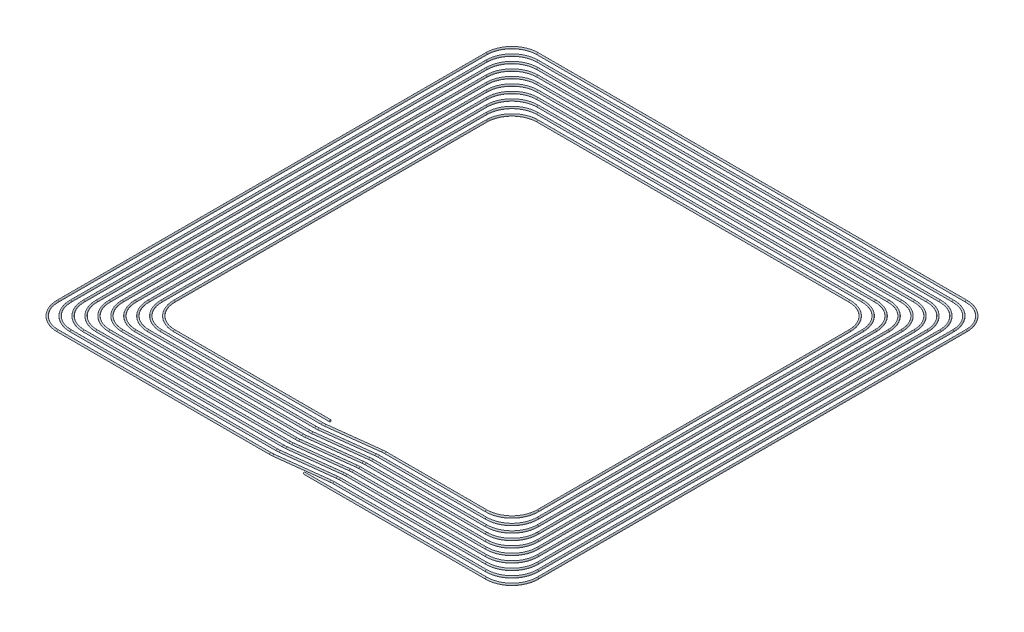
SolidWorks part; units mm, degrees
ref_plane "前视基准面" through (0, 0, 0) normal (0, 0, 1) x (1, 0, 0)
ref_plane "上视基准面" through (0, 0, 0) normal (0, 1, 0) x (1, 0, 0)
ref_plane "右视基准面" through (0, 0, 0) normal (1, 0, 0) x (0, 0, -1)
sketch "草图1" plane through (0, 0, 0) normal (0, 1, 0) x (1, 0, 0)
  line L0 (18.78, -3.78) -> (261.22, -3.78)
  line L1 (15, 0) -> (265, 0)
  line L2 (0, -15) -> (0, -265)
  line L3 (15, -280) -> (139.1015, -280)
  line L4 (280, -15) -> (280, -265)
  line L5 (276.22, -18.78) -> (276.22, -261.22)
  line L6 (18.78, -276.22) -> (139.1015, -276.22)
  line L7 (3.78, -18.78) -> (3.78, -261.22)
  line L8 (22.56, -7.56) -> (257.44, -7.56)
  line L9 (272.44, -22.56) -> (272.44, -257.44)
  line L10 (22.56, -272.44) -> (139.1015, -272.44)
  line L11 (7.56, -22.56) -> (7.56, -257.44)
  line L12 (26.34, -11.34) -> (253.66, -11.34)
  line L13 (268.66, -26.34) -> (268.66, -253.66)
  line L14 (26.34, -268.66) -> (139.1015, -268.66)
  line L15 (11.34, -26.34) -> (11.34, -253.66)
  line L16 (30.12, -15.12) -> (249.88, -15.12)
  line L17 (264.88, -30.12) -> (264.88, -249.88)
  line L18 (30.12, -264.88) -> (139.1015, -264.88)
  line L19 (15.12, -30.12) -> (15.12, -249.88)
  line L20 (15, -276.22) -> (265, -276.22) construction
  line L21 (3.78, -15) -> (3.78, -265) construction
  line L22 (7.56, -15) -> (7.56, -265) construction
  line L23 (15, -272.44) -> (265, -272.44) construction
  line L24 (15, -268.66) -> (265, -268.66) construction
  line L25 (11.34, -15) -> (11.34, -265) construction
  line L26 (15.12, -15.12) -> (15.12, -264.88) construction
  line L27 (15.12, -264.88) -> (264.88, -264.88) construction
  line L28 (15, -280) -> (265, -280) construction
  line L29 (280, -15) -> (280, -265) construction
  line L30 (276.22, -15) -> (276.22, -265) construction
  line L31 (272.44, -15) -> (272.44, -265) construction
  line L32 (268.66, -15) -> (268.66, -265) construction
  line L33 (264.88, -15.12) -> (264.88, -264.88) construction
  line L34 (15, -3.78) -> (265, -3.78) construction
  line L35 (15, -7.56) -> (265, -7.56) construction
  line L36 (15, -11.34) -> (265, -11.34) construction
  line L37 (15.12, -15.12) -> (264.88, -15.12) construction
  line L38 (33.9, -18.9) -> (246.1, -18.9)
  line L39 (261.1, -33.9) -> (261.1, -246.1)
  line L40 (33.9, -261.1) -> (139.1015, -261.1)
  line L41 (18.9, -33.9) -> (18.9, -246.1)
  line L42 (37.68, -22.68) -> (242.32, -22.68)
  line L43 (257.32, -37.68) -> (257.32, -242.32)
  line L44 (37.68, -257.32) -> (139.1015, -257.32)
  line L45 (22.68, -37.68) -> (22.68, -242.32)
  line L46 (41.46, -26.46) -> (238.54, -26.46)
  line L47 (253.54, -41.46) -> (253.54, -238.54)
  line L48 (41.46, -253.54) -> (139.1015, -253.54)
  line L49 (26.46, -41.46) -> (26.46, -238.54)
  line L50 (45.24, -30.24) -> (234.76, -30.24)
  line L51 (249.76, -45.24) -> (249.76, -234.76)
  line L52 (45.24, -249.76) -> (139.1015, -249.76)
  line L53 (30.24, -45.24) -> (30.24, -234.76)
  line L54 (49.02, -34.02) -> (230.98, -34.02)
  line L55 (245.98, -49.02) -> (245.98, -230.98)
  line L56 (49.02, -245.98) -> (140, -245.98)
  line L57 (34.02, -49.02) -> (34.02, -230.98)
  line L58 (34.02, -34.02) -> (245.98, -34.02) construction
  line L59 (245.98, -34.02) -> (245.98, -245.98) construction
  line L60 (30.24, -30.24) -> (249.76, -30.24) construction
  line L61 (249.76, -30.24) -> (249.76, -249.76) construction
  line L62 (30.12, -26.46) -> (249.88, -26.46) construction
  line L63 (253.54, -30.12) -> (253.54, -249.88) construction
  line L64 (30.12, -22.68) -> (249.88, -22.68) construction
  line L65 (257.32, -30.12) -> (257.32, -249.88) construction
  line L66 (30.12, -18.9) -> (249.88, -18.9) construction
  line L67 (261.1, -30.12) -> (261.1, -249.88) construction
  line L68 (34.02, -245.98) -> (245.98, -245.98) construction
  line L69 (30.24, -249.76) -> (249.76, -249.76) construction
  line L70 (30.12, -253.54) -> (249.88, -253.54) construction
  line L71 (30.12, -257.32) -> (249.88, -257.32) construction
  line L72 (30.12, -261.1) -> (249.88, -261.1) construction
  line L73 (34.02, -34.02) -> (34.02, -245.98) construction
  line L74 (30.24, -30.24) -> (30.24, -249.76) construction
  line L75 (26.46, -30.12) -> (26.46, -249.88) construction
  line L76 (22.68, -30.12) -> (22.68, -249.88) construction
  line L77 (18.9, -30.12) -> (18.9, -249.88) construction
  line L78 (140.8921, -279.8927) -> (170.5473, -276.3273)
  line L79 (140, -281.3464) -> (140, -242.32) construction
  line L80 (158.8189, -280) -> (265, -280)
  line L81 (140.8921, -276.1127) -> (170.5473, -272.5473)
  line L82 (140.8921, -272.3327) -> (170.5473, -268.7673)
  line L83 (140.8921, -268.5527) -> (170.5473, -264.9873)
  line L84 (140.8921, -264.7727) -> (170.5473, -261.2073)
  line L85 (172.3379, -249.76) -> (234.76, -249.76)
  line L86 (140.8921, -253.4327) -> (170.5473, -249.8673)
  line L87 (140.8921, -249.6527) -> (170.5473, -246.0873)
  line L88 (140.8921, -260.9927) -> (170.5473, -257.4273)
  line L89 (140.8921, -257.2127) -> (170.5473, -253.6473)
  line L90 (172.3379, -245.98) -> (230.98, -245.98)
  line L91 (172.3379, -253.54) -> (238.54, -253.54)
  line L92 (172.3379, -257.32) -> (242.32, -257.32)
  line L93 (172.3379, -261.1) -> (246.1, -261.1)
  line L94 (172.3379, -264.88) -> (249.88, -264.88)
  line L95 (172.3379, -268.66) -> (253.66, -268.66)
  line L96 (30.12, -264.88) -> (249.88, -264.88) construction
  line L97 (172.3379, -272.44) -> (257.44, -272.44)
  line L98 (172.3379, -276.22) -> (261.22, -276.22)
  arc A0 (0, -265) -> (15, -280) centre (15, -265) ccw
  arc A1 (265, -280) -> (280, -265) centre (265, -265) ccw
  arc A2 (265, 0) -> (280, -15) centre (265, -15) cw
  arc A3 (15, 0) -> (0, -15) centre (15, -15) ccw
  arc A4 (139.1015, -261.1) -> (140.8921, -260.9927) centre (139.1015, -246.1) ccw
  arc A5 (139.1015, -264.88) -> (140.8921, -264.7727) centre (139.1015, -249.88) ccw
  arc A6 (139.1015, -268.66) -> (140.8921, -268.5527) centre (139.1015, -253.66) ccw
  arc A7 (139.1015, -272.44) -> (140.8921, -272.3327) centre (139.1015, -257.44) ccw
  arc A8 (139.1015, -276.22) -> (140.8921, -276.1127) centre (139.1015, -261.22) ccw
  arc A9 (139.1015, -280) -> (140.8921, -279.8927) centre (139.1015, -265) ccw
  arc A10 (170.5473, -276.3273) -> (172.3379, -276.22) centre (172.3379, -291.22) cw
  arc A11 (170.5473, -272.5473) -> (172.3379, -272.44) centre (172.3379, -287.44) cw
  arc A12 (170.5473, -268.7673) -> (172.3379, -268.66) centre (172.3379, -283.66) cw
  arc A13 (170.5473, -264.9873) -> (172.3379, -264.88) centre (172.3379, -279.88) cw
  arc A14 (170.5473, -261.2073) -> (172.3379, -261.1) centre (172.3379, -276.1) cw
  arc A15 (170.5473, -257.4273) -> (172.3379, -257.32) centre (172.3379, -272.32) cw
  arc A16 (30.12, -15.12) -> (15.12, -30.12) centre (30.12, -30.12) ccw
  arc A17 (276.22, -18.78) -> (261.22, -3.78) centre (261.22, -18.78) ccw
  arc A18 (265, -280) -> (280, -265) centre (265, -265) ccw
  arc A19 (26.34, -11.34) -> (11.34, -26.34) centre (26.34, -26.34) ccw
  arc A20 (18.78, -276.22) -> (3.78, -261.22) centre (18.78, -261.22) cw
  arc A21 (7.56, -257.44) -> (22.56, -272.44) centre (22.56, -257.44) ccw
  arc A22 (26.34, -268.66) -> (11.34, -253.66) centre (26.34, -253.66) cw
  arc A23 (15.12, -249.88) -> (30.12, -264.88) centre (30.12, -249.88) ccw
  arc A24 (15.12, -264.88) -> (15.12, -264.88) centre (15.12, -264.88) ccw construction
  arc A25 (261.22, -276.22) -> (276.22, -261.22) centre (261.22, -261.22) ccw
  arc A26 (257.44, -272.44) -> (272.44, -257.44) centre (257.44, -257.44) ccw
  arc A27 (253.66, -268.66) -> (268.66, -253.66) centre (253.66, -253.66) ccw
  arc A28 (249.88, -264.88) -> (264.88, -249.88) centre (249.88, -249.88) ccw
  arc A29 (264.88, -264.88) -> (264.88, -264.88) centre (264.88, -264.88) ccw construction
  arc A30 (272.44, -22.56) -> (257.44, -7.56) centre (257.44, -22.56) ccw
  arc A31 (268.66, -26.34) -> (253.66, -11.34) centre (253.66, -26.34) ccw
  arc A32 (249.88, -15.12) -> (264.88, -30.12) centre (249.88, -30.12) cw
  arc A33 (264.88, -15.12) -> (264.88, -15.12) centre (264.88, -15.12) cw construction
  arc A34 (15.12, -15.12) -> (15.12, -15.12) centre (15.12, -15.12) ccw construction
  arc A35 (22.56, -7.56) -> (7.56, -22.56) centre (22.56, -22.56) ccw
  arc A36 (18.78, -3.78) -> (3.78, -18.78) centre (18.78, -18.78) ccw
  arc A37 (15, -3.78) -> (3.78, -15) centre (15, -15) ccw construction
  arc A38 (15, -7.56) -> (7.56, -15) centre (15, -15) ccw construction
  arc A39 (15, -11.34) -> (11.34, -15) centre (15, -15) ccw construction
  arc A40 (265, -3.78) -> (276.22, -15) centre (265, -15) cw construction
  arc A41 (265, -7.56) -> (272.44, -15) centre (265, -15) cw construction
  arc A42 (265, -11.34) -> (268.66, -15) centre (265, -15) cw construction
  arc A43 (265, -272.44) -> (272.44, -265) centre (265, -265) ccw construction
  arc A44 (265, -276.22) -> (276.22, -265) centre (265, -265) ccw construction
  arc A45 (265, -268.66) -> (268.66, -265) centre (265, -265) ccw construction
  arc A46 (3.78, -265) -> (15, -276.22) centre (15, -265) ccw construction
  arc A47 (7.56, -265) -> (15, -272.44) centre (15, -265) ccw construction
  arc A48 (11.34, -265) -> (15, -268.66) centre (15, -265) ccw construction
  arc A49 (170.5473, -253.6473) -> (172.3379, -253.54) centre (172.3379, -268.54) cw
  arc A50 (139.1015, -257.32) -> (140.8921, -257.2127) centre (139.1015, -242.32) ccw
  arc A51 (139.1015, -253.54) -> (140.8921, -253.4327) centre (139.1015, -238.54) ccw
  arc A52 (170.5473, -249.8673) -> (172.3379, -249.76) centre (172.3379, -264.76) cw
  arc A53 (234.76, -30.24) -> (249.76, -45.24) centre (234.76, -45.24) cw
  arc A54 (234.76, -249.76) -> (249.76, -234.76) centre (234.76, -234.76) ccw
  arc A55 (30.24, -234.76) -> (45.24, -249.76) centre (45.24, -234.76) ccw
  arc A56 (45.24, -30.24) -> (30.24, -45.24) centre (45.24, -45.24) ccw
  arc A57 (230.98, -34.02) -> (245.98, -49.02) centre (230.98, -49.02) cw
  arc A58 (245.98, -34.02) -> (245.98, -34.02) centre (245.98, -34.02) cw construction
  arc A59 (238.54, -26.46) -> (253.54, -41.46) centre (238.54, -41.46) cw
  arc A60 (242.32, -22.68) -> (257.32, -37.68) centre (242.32, -37.68) cw
  arc A61 (246.1, -18.9) -> (261.1, -33.9) centre (246.1, -33.9) cw
  arc A62 (230.98, -245.98) -> (245.98, -230.98) centre (230.98, -230.98) ccw
  arc A63 (245.98, -245.98) -> (245.98, -245.98) centre (245.98, -245.98) ccw construction
  arc A64 (238.54, -253.54) -> (253.54, -238.54) centre (238.54, -238.54) ccw
  arc A65 (242.32, -257.32) -> (257.32, -242.32) centre (242.32, -242.32) ccw
  arc A66 (246.1, -261.1) -> (261.1, -246.1) centre (246.1, -246.1) ccw
  arc A67 (49.02, -245.98) -> (34.02, -230.98) centre (49.02, -230.98) cw
  arc A68 (34.02, -245.98) -> (34.02, -245.98) centre (34.02, -245.98) ccw construction
  arc A69 (41.46, -253.54) -> (26.46, -238.54) centre (41.46, -238.54) cw
  arc A70 (22.68, -242.32) -> (37.68, -257.32) centre (37.68, -242.32) ccw
  arc A71 (33.9, -261.1) -> (18.9, -246.1) centre (33.9, -246.1) cw
  arc A72 (49.02, -34.02) -> (34.02, -49.02) centre (49.02, -49.02) ccw
  arc A73 (34.02, -34.02) -> (34.02, -34.02) centre (34.02, -34.02) ccw construction
  arc A74 (41.46, -26.46) -> (26.46, -41.46) centre (41.46, -41.46) ccw
  arc A75 (37.68, -22.68) -> (22.68, -37.68) centre (37.68, -37.68) ccw
  arc A76 (33.9, -18.9) -> (18.9, -33.9) centre (33.9, -33.9) ccw
  arc A77 (30.12, -18.9) -> (18.9, -30.12) centre (30.12, -30.12) ccw construction
  arc A78 (30.12, -22.68) -> (22.68, -30.12) centre (30.12, -30.12) ccw construction
  arc A79 (30.12, -26.46) -> (26.46, -30.12) centre (30.12, -30.12) ccw construction
  arc A80 (249.88, -18.9) -> (261.1, -30.12) centre (249.88, -30.12) cw construction
  arc A81 (249.88, -22.68) -> (257.32, -30.12) centre (249.88, -30.12) cw construction
  arc A82 (249.88, -26.46) -> (253.54, -30.12) centre (249.88, -30.12) cw construction
  arc A83 (249.88, -257.32) -> (257.32, -249.88) centre (249.88, -249.88) ccw construction
  arc A84 (249.88, -253.54) -> (253.54, -249.88) centre (249.88, -249.88) ccw construction
  arc A85 (249.88, -261.1) -> (261.1, -249.88) centre (249.88, -249.88) ccw construction
  arc A86 (26.46, -249.88) -> (30.12, -253.54) centre (30.12, -249.88) ccw construction
  arc A87 (22.68, -249.88) -> (30.12, -257.32) centre (30.12, -249.88) ccw construction
  arc A88 (18.9, -249.88) -> (30.12, -261.1) centre (30.12, -249.88) ccw construction
  arc A89 (30.24, -249.76) -> (30.24, -249.76) centre (30.24, -249.76) ccw construction
  arc A90 (249.76, -249.76) -> (249.76, -249.76) centre (249.76, -249.76) ccw construction
  arc A91 (30.24, -30.24) -> (30.24, -30.24) centre (30.24, -30.24) ccw construction
  arc A92 (249.76, -30.24) -> (249.76, -30.24) centre (249.76, -30.24) cw construction
  arc A93 (170.5473, -246.0873) -> (172.3379, -245.98) centre (172.3379, -260.98) cw
  arc A94 (139.1015, -249.76) -> (140.8921, -249.6527) centre (139.1015, -234.76) ccw
  point P7 (0, -280)
  point P12 (280, 0)
  point P15 (0, 0)
  point P259 (140, -261.1)
  point P262 (140, -264.88)
  point P265 (140, -268.66)
  point P268 (140, -272.44)
  point P271 (140, -276.22)
  point P274 (140, -280)
  point P277 (171.4394, -276.22)
  point P292 (140, -257.32)
  point P295 (140, -253.54)
  point P302 (140, -249.76)
  dimension "D3" = 15
  dimension "D8" = 15
  dimension "D14" = 15
  dimension "D15" = 15
  dimension "D1" = 280
  dimension "D2" = 280
  dimension "D4" = 3.78
  dimension "D5" = 3.78
  dimension "D6" = 3.78
  dimension "D7" = 3.78
  dimension "D9" = 3.78
  dimension "D10" = 3.78
  dimension "D11" = 3.78
  dimension "D12" = 3.78
  dimension "D13" = 3.78
ref_plane "基准面1" through (140, 0, 0) normal (1, 0, 0) x (0, 0, -1)
sketch "草图2" plane through (140, 0, 0) normal (1, 0, 0) x (0, 0, -1)
  line L0 (-281.3464, 0) -> (-242.32, 0) construction
  circle A0 centre (-245.9752, 0) radius 0.5
sweep "扫描1" add profiles "草图2" path "草图1"
